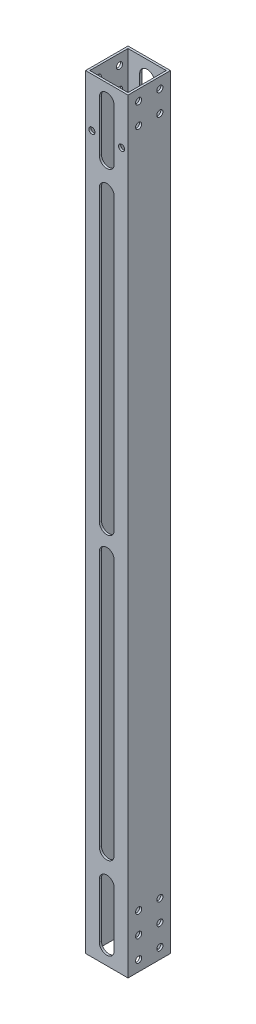
SolidWorks part; units mm, degrees
material "6061 合金"
ref_plane "前视基准面" through (0, 0, 0) normal (0, 0, 1) x (1, 0, 0)
ref_plane "上视基准面" through (0, 0, 0) normal (0, 1, 0) x (1, 0, 0)
ref_plane "右视基准面" through (0, 0, 0) normal (1, 0, 0) x (0, 0, -1)
sketch "草图1" plane through (0, 0, 0) normal (0, 0, 1) x (1, 0, 0)
  line L0 (0, 0) -> (0, 360)
  dimension "D1" = 360
other "铝管 20X20X1(1)"
ref_plane "基准面4" through (0, 0, 0) normal (0, 1, 0) x (-1, 0, 0)
sketch "草图11" plane through (0, 0, 0) normal (0, 1, 0) x (-1, 0, 0)
  line L1 (-10, -10) -> (10, -10)
  line L2 (-10, -10) -> (-10, 10)
  line L3 (-10, 10) -> (10, 10)
  line L4 (10, -10) -> (10, 10)
  line L5 (-10, -10) -> (10, 10) construction
  line L6 (-10, 10) -> (10, -10) construction
  line L7 (-9, -9) -> (9, -9)
  line L8 (-9, -9) -> (-9, 9)
  line L9 (-9, 9) -> (9, 9)
  line L10 (9, -9) -> (9, 9)
  line L11 (-9, -9) -> (9, 9) construction
  line L12 (-9, 9) -> (9, -9) construction
  point P0 (0, 0)
  point P6 (0, 0)
  point P11 (0, 0)
  dimension "D1" = 20
  dimension "D2" = 20
  dimension "D3" = 18
  dimension "D4" = 18
sketch "草图12" plane through (10, 0, 0) normal (1, 0, 0) x (0, 0, -1)
  line L0 (-10, 360) -> (10, 360) construction
  line L1 (10, 360) -> (10, 0) construction
  line L2 (-10, 360) -> (-10, 0) construction
  line L3 (0, 0) -> (0, 360) construction
  line L4 (-10, 0) -> (10, 0) construction
  line L5 (0, 360) -> (0, 0) construction
  circle A0 centre (-5, 355) radius 1.45
  circle A1 centre (5, 355) radius 1.45
  circle A2 centre (-5, 345) radius 1.45
  circle A3 centre (5, 345) radius 1.45
  circle A4 centre (5, 5) radius 1.45
  circle A5 centre (5, 15) radius 1.45
  circle A6 centre (5, 25) radius 1.45
  circle A7 centre (-5, 5) radius 1.45
  circle A8 centre (-5, 15) radius 1.45
  circle A9 centre (-5, 25) radius 1.45
  dimension "D1" = 5
  dimension "D3" = 5
  dimension "D4" = 10
  dimension "D5" = 5
  dimension "D6" = 10
  dimension "D7" = 5
  dimension "D8" = 5
  dimension "D9" = 2.9
  dimension "D10" = 5
  dimension "D11" = 5
  dimension "D12" = 2.9
  dimension "D13" = 10
  dimension "D14" = 10
  dimension "D2" = 5
extrude "切除-拉伸1" cut sketch "草图12" against normal blind 34
sketch "草图13" plane through (0, 0, 10) normal (0, 0, 1) x (1, 0, 0)
  line L0 (0, 360) -> (0, 0) construction
  line L1 (-10, 360) -> (10, 360) construction
  line L2 (-7, 337) -> (7, 337) construction
  circle A0 centre (-7, 337) radius 1.45
  circle A1 centre (7, 337) radius 1.45
  point P8 (0, 337)
  dimension "D3" = 2.9
  dimension "D1" = 14
  dimension "D2" = 23
extrude "切除-拉伸2" cut sketch "草图13" against normal through all
sketch "草图14" plane through (0, 0, 10) normal (0, 0, 1) x (1, 0, 0)
  circle A0 centre (-7, 337) radius 3.5
  circle A1 centre (7, 337) radius 3.5
  dimension "D1" = 7
sketch "草图15" plane through (0, 0, 10) normal (0, 0, 1) x (1, 0, 0)
  line L0 (0, 0) -> (0, 360) construction
  line L1 (-10, 360) -> (10, 360) construction
  line L2 (0, 33.5081) -> (0, 7.837) construction
  line L3 (3.5, 33.5081) -> (3.5, 7.837)
  line L4 (-3.5, 33.5081) -> (-3.5, 7.837)
  line L5 (0, 46.6536) -> (0, 167.1187) construction
  line L6 (-3.5, 46.6536) -> (-3.5, 167.1187)
  line L7 (3.5, 46.6536) -> (3.5, 167.1187)
  line L8 (0, 179.2323) -> (0, 315.4723) construction
  line L9 (-3.5, 179.2323) -> (-3.5, 315.4723)
  line L10 (3.5, 179.2323) -> (3.5, 315.4723)
  line L11 (0, 328.5622) -> (0, 352.5139) construction
  line L12 (-3.5, 328.5622) -> (-3.5, 352.5139)
  line L13 (3.5, 328.5622) -> (3.5, 352.5139)
  arc A0 (3.5, 33.5081) -> (-3.5, 33.5081) centre (0, 33.5081) ccw
  arc A1 (-3.5, 7.837) -> (3.5, 7.837) centre (0, 7.837) ccw
  arc A2 (-3.5, 46.6536) -> (3.5, 46.6536) centre (0, 46.6536) ccw
  arc A3 (3.5, 167.1187) -> (-3.5, 167.1187) centre (0, 167.1187) ccw
  arc A4 (-3.5, 179.2323) -> (3.5, 179.2323) centre (0, 179.2323) ccw
  arc A5 (3.5, 315.4723) -> (-3.5, 315.4723) centre (0, 315.4723) ccw
  arc A6 (-3.5, 328.5622) -> (3.5, 328.5622) centre (0, 328.5622) ccw
  arc A7 (3.5, 352.5139) -> (-3.5, 352.5139) centre (0, 352.5139) ccw
  point P7 (0, 20.6725)
  point P12 (0, 106.8862)
  point P19 (0, 247.3523)
  point P26 (0, 340.5381)
  dimension "D1" = 7
  dimension "D2" = 7
  dimension "D3" = 7
  dimension "D4" = 7
extrude "切除-拉伸3" cut sketch "草图15" against normal through all
